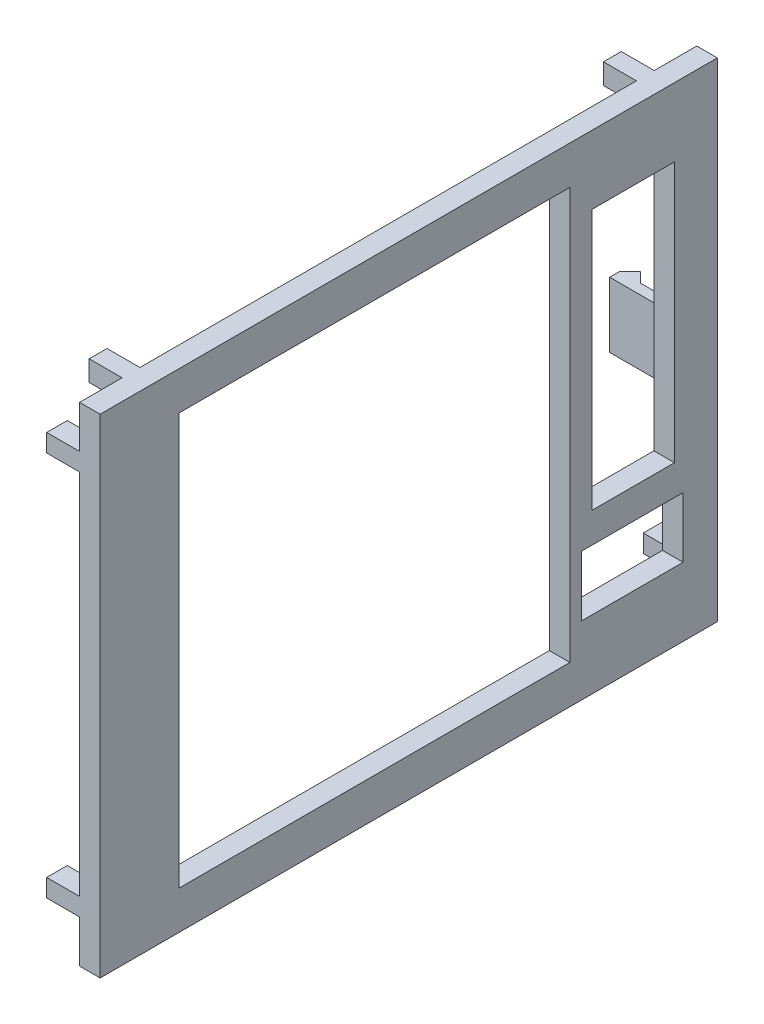
SolidWorks part; units mm, degrees
ref_plane "Front Plane" through (0, 0, 0) normal (0, 0, 1) x (1, 0, 0)
ref_plane "Top Plane" through (0, 0, 0) normal (0, 1, 0) x (1, 0, 0)
ref_plane "Right Plane" through (0, 0, 0) normal (1, 0, 0) x (0, 0, -1)
sketch "Sketch1" plane through (0, 0, 0) normal (1, 0, 0) x (0, 0, -1)
  line L1 (0, 0) -> (90, 0)
  line L2 (0, 0) -> (0, 71.2)
  line L3 (0, 71.2) -> (90, 71.2)
  line L4 (90, 0) -> (90, 71.2)
  dimension "D1" = 71.2
  dimension "D2" = 90
extrude "Boss-Extrude1" add sketch "Sketch1" along normal blind 3
sketch "Sketch2" plane through (0, 0, 0) normal (-1, 0, 0) x (0, 0, 1)
  line L0 (-90, 0) -> (-90, 71.2) construction
  line L1 (-90, 65) -> (-87, 65)
  line L2 (-90, 65) -> (-90, 62.4)
  line L3 (-90, 62.4) -> (-87, 62.4)
  line L4 (-87, 65) -> (-87, 62.4)
  line L5 (-90, 71.2) -> (0, 71.2) construction
  line L6 (-83.8, 71.2) -> (-81.2, 71.2)
  line L7 (-83.8, 71.2) -> (-83.8, 68.2)
  line L8 (-83.8, 68.2) -> (-81.2, 68.2)
  line L9 (-81.2, 71.2) -> (-81.2, 68.2)
  line L10 (0, 71.2) -> (0, 0) construction
  line L11 (-8.8, 71.2) -> (-6.2, 71.2)
  line L12 (-8.8, 71.2) -> (-8.8, 68.2)
  line L13 (-8.8, 68.2) -> (-6.2, 68.2)
  line L14 (-6.2, 71.2) -> (-6.2, 68.2)
  line L15 (0, 65) -> (-3, 65)
  line L16 (0, 65) -> (0, 62.4)
  line L17 (0, 62.4) -> (-3, 62.4)
  line L18 (-3, 65) -> (-3, 62.4)
  line L19 (0, 0) -> (-90, 0) construction
  line L20 (0, 8.8) -> (-3, 8.8)
  line L21 (0, 8.8) -> (0, 6.2)
  line L22 (0, 6.2) -> (-3, 6.2)
  line L23 (-3, 8.8) -> (-3, 6.2)
  line L24 (-6.2, 0) -> (-8.8, 0)
  line L25 (-6.2, 0) -> (-6.2, 3)
  line L26 (-6.2, 3) -> (-8.8, 3)
  line L27 (-8.8, 0) -> (-8.8, 3)
  line L28 (-90, 8.8) -> (-87, 8.8)
  line L29 (-90, 8.8) -> (-90, 6.2)
  line L30 (-90, 6.2) -> (-87, 6.2)
  line L31 (-87, 8.8) -> (-87, 6.2)
  line L32 (-83.8, 0) -> (-81.2, 0)
  line L33 (-83.8, 0) -> (-83.8, 3)
  line L34 (-83.8, 3) -> (-81.2, 3)
  line L35 (-81.2, 0) -> (-81.2, 3)
  dimension "D1" = 3
  dimension "D2" = 6.2
  dimension "D3" = 6.2
  dimension "D4" = 6.2
  dimension "D5" = 6.2
  dimension "D6" = 3
  dimension "D7" = 2.6
  dimension "D8" = 3
  dimension "D9" = 2.6
  dimension "D10" = 2.6
  dimension "D11" = 3
  dimension "D12" = 3
  dimension "D13" = 2.6
  dimension "D14" = 2.6
  dimension "D15" = 3
  dimension "D16" = 2.6
  dimension "D17" = 3
  dimension "D18" = 3
  dimension "D19" = 2.6
extrude "Boss-Extrude2" add sketch "Sketch2" along normal blind 4.8
sketch "Sketch4" plane through (3, 0, 0) normal (1, 0, 0) x (0, 0, -1)
  line L0 (0, 71.2) -> (0, 0) construction
  line L1 (11.5, 65.6) -> (68.5, 65.6)
  line L2 (11.5, 65.6) -> (11.5, 5.6)
  line L3 (11.5, 5.6) -> (68.5, 5.6)
  line L4 (68.5, 65.6) -> (68.5, 5.6)
  point P4 (11.5, 35.6)
  point P7 (0, 35.6)
  dimension "D1" = 60
  dimension "D2" = 57
  dimension "D3" = 11.5
extrude "Cut-Extrude1" cut sketch "Sketch4" against normal up to next
sketch "Sketch5" plane through (3, 0, 0) normal (1, 0, 0) x (0, 0, -1)
  line L0 (90, 0) -> (90, 71.2) construction
  line L1 (85, 10) -> (70.2, 10)
  line L2 (85, 10) -> (85, 18.8)
  line L3 (85, 18.8) -> (70.2, 18.8)
  line L4 (70.2, 10) -> (70.2, 18.8)
  line L5 (90, 71.2) -> (0, 71.2) construction
  line L6 (83.75, 61.2) -> (71.75, 61.2)
  line L7 (83.75, 61.2) -> (83.75, 23.2)
  line L8 (83.75, 23.2) -> (71.75, 23.2)
  line L9 (71.75, 61.2) -> (71.75, 23.2)
  line L10 (0, 0) -> (90, 0) construction
  dimension "D1" = 8.8
  dimension "D2" = 14.8
  dimension "D3" = 5
  dimension "D4" = 12
  dimension "D5" = 38
  dimension "D6" = 10
  dimension "D7" = 10
  dimension "D8" = 6.25
extrude "Cut-Extrude2" cut sketch "Sketch5" against normal up to next
sketch "Sketch6" plane through (0, 0, 0) normal (-1, 0, 0) x (0, 0, 1)
  line L0 (-90, 8.8) -> (-90, 62.4) construction
  line L1 (-86.8, 40.35) -> (-85.3, 40.35)
  line L2 (-86.8, 40.35) -> (-86.8, 30.85)
  line L3 (-86.8, 30.85) -> (-85.3, 30.85)
  line L4 (-85.3, 40.35) -> (-85.3, 30.85)
  point P10 (-90, 35.6)
  point P11 (-86.8, 35.6)
  dimension "D1" = 3.2
  dimension "D3" = 1.5
  dimension "D4" = 9.5
extrude "Boss-Extrude3" add sketch "Sketch6" along normal blind 8
sketch "Sketch7" plane through (0, 30.85, 0) normal (0, -1, 0) x (1, 0, 0)
  line L0 (-8, -86.8) -> (-6.5, -88.3)
  line L1 (-6.5, -88.3) -> (-5, -86.8)
  line L2 (-8, -86.8) -> (0, -86.8) construction
  line L3 (-5, -86.8) -> (-8, -86.8)
  dimension "D1" = 3
extrude "Boss-Extrude4" add sketch "Sketch7" against normal up to surface (9.5 mm away) up to face at (-4, 40.35, -86.05)
